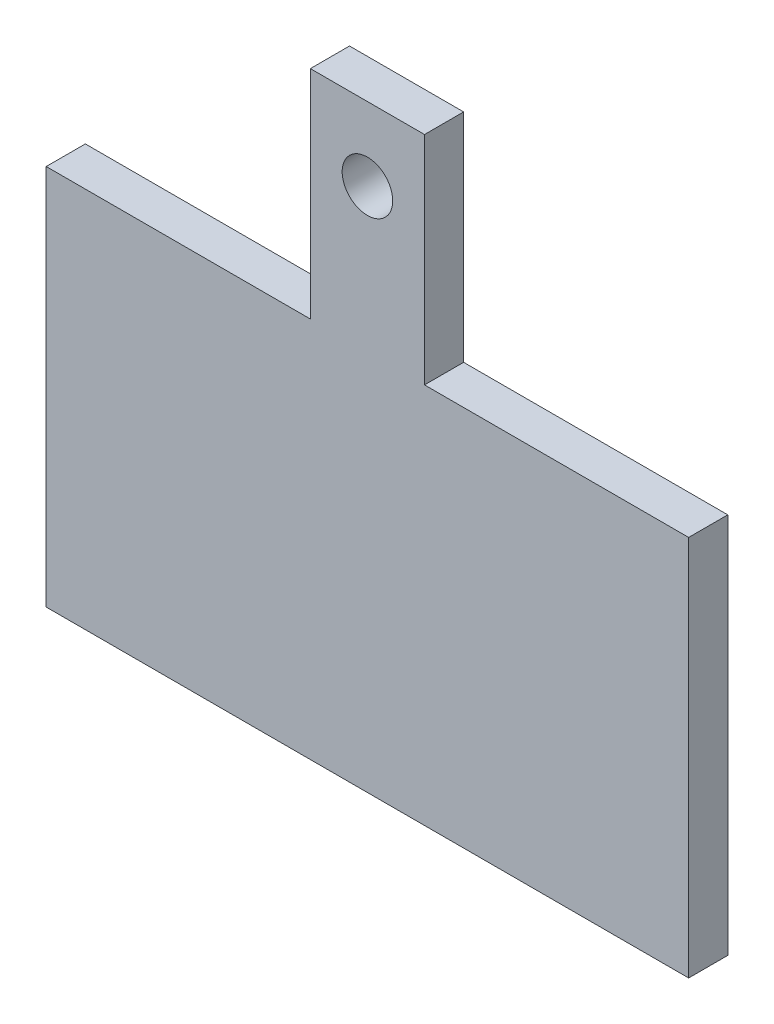
SolidWorks part; units mm, degrees
ref_plane "Front Plane" through (0, 0, 0) normal (0, 0, 1) x (1, 0, 0)
ref_plane "Top Plane" through (0, 0, 0) normal (0, 1, 0) x (1, 0, 0)
ref_plane "Right Plane" through (0, 0, 0) normal (1, 0, 0) x (0, 0, -1)
other "Configuration Table"
sketch "Sketch2" plane through (0, 0, 0) normal (0, 0, 1) x (1, 0, 0)
  line L1 (-19.7, -11.7) -> (19.7, -11.7)
  line L2 (-19.7, -11.7) -> (-19.7, 11.7)
  line L3 (-19.7, 11.7) -> (19.7, 11.7)
  line L4 (19.7, -11.7) -> (19.7, 11.7)
extrude "Hatch_plate" add sketch "Sketch2" along normal blind 2.4 from offset 0
sketch "Sketch3" plane through (0, 0, 0) normal (0, 0, 1) x (1, 0, 0)
  line L1 (-3.5, 11) -> (3.5, 11)
  line L2 (-3.5, 11) -> (-3.5, 25)
  line L3 (-3.5, 25) -> (3.5, 25)
  line L4 (3.5, 11) -> (3.5, 25)
  circle A0 centre (0, 20.5) radius 1.55
extrude "Drive_arm_D3p1" add sketch "Sketch3" along normal blind 2.4 from offset 0
